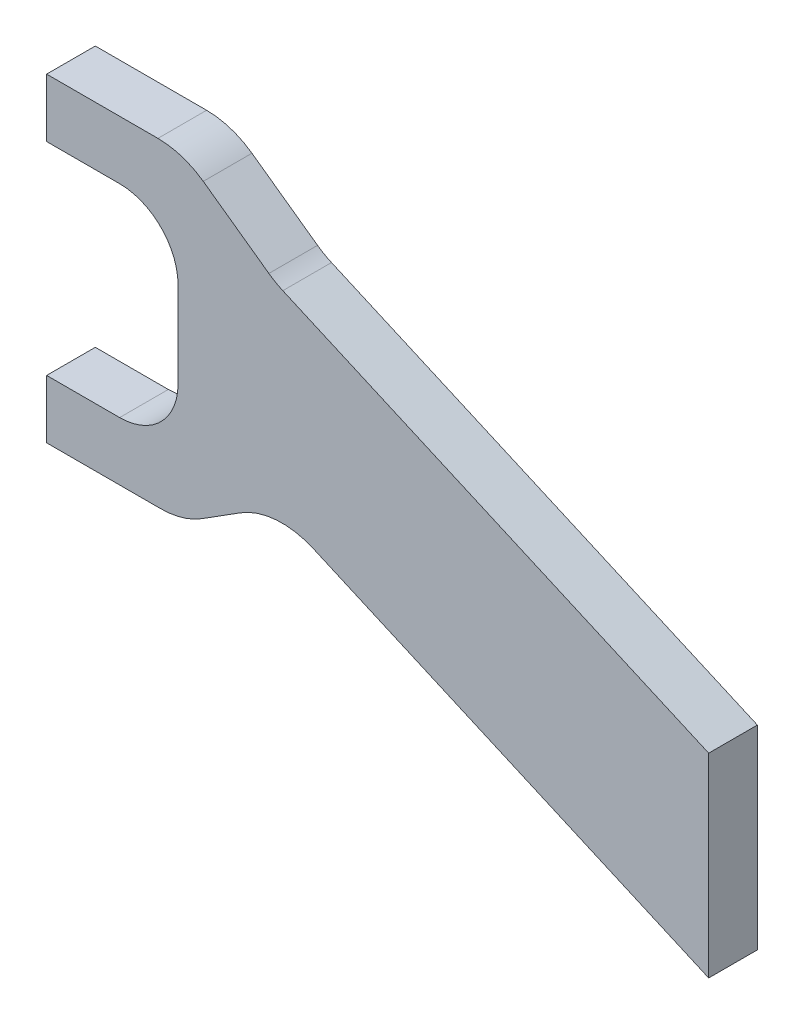
SolidWorks part; units mm, degrees
material "PBT General Purpose"
ref_plane "Front Plane" through (0, 0, 0) normal (0, 0, 1) x (1, 0, 0)
ref_plane "Top Plane" through (0, 0, 0) normal (0, 1, 0) x (1, 0, 0)
ref_plane "Right Plane" through (0, 0, 0) normal (1, 0, 0) x (0, 0, -1)
sketch "frame_outline" plane through (0, 0, 0) normal (0, 0, 1) x (1, 0, 0)
  line L89 (0, 1.64) -> (0, 1.34)
  line L99 (0, 1.34) -> (0.675, 1.34)
  line L100 (0.675, 1.34) -> (0.675, 0.3)
  line L101 (0.675, 0.3) -> (0, 0.3)
  line L102 (0, 0.3) -> (0, 0)
  line L103 (0, 0) -> (0.7, 0)
  line L104 (0.7, 0) -> (1.175, 0.3)
  line L105 (1.175, 0.3) -> (3.4, -0.68)
  line L106 (3.4, -0.68) -> (3.4, 0.32)
  line L107 (3.4, 0.32) -> (1.175, 1.3)
  line L108 (1.175, 1.3) -> (0.7, 1.64)
  line L109 (0.7, 1.64) -> (0, 1.64)
  line L110 (0.675, 0.82) -> (3.9765, 0.82) construction
  point P24 (3.4, -0.18)
  dimension "D1" = 0.3
  dimension "D2" = 0.3
  dimension "D9" = 1.64
  dimension "D10" = 0.675
  dimension "D11" = 1
  dimension "D12" = 1
  dimension "D14" = 0.7
  dimension "D15" = 0.7
  dimension "D16" = 0.5
  dimension "D3" = 3.4
extrude "Boss-Extrude1" add sketch "frame_outline" along normal mid plane 0.25
fillet "Fillet1" radius 0.3 2 edges at (0.675, 0.3, 0) (0.675, 1.34, 0)
fillet "Fillet2" radius 0.4 4 edges at (0.7, 0, 0) (1.175, 0.3, 0) (1.175, 1.3, 0) (0.7, 1.64, 0)
equation "\"t\"= 0.25'thickness of the sheets"
equation "\"t_cf\"= 0.115'thickness of single carbon fiber layer"
equation "\"t_kapton\"= 0.025'thickness of single Kapton flex layer"
equation "\"t_fr4\"= 0.1'thickness of FR4 with copper layer"
equation "\"joint_flex\"= 0.1'Width of flextures gap"
equation "\"joint_flex_eff\"= 0.02'Width of flecture after castelation"
equation "\"joint_fold\"= 0.2'Width of folding joints for 90deg fold"
equation "\"gap_tolerance\"= 0.002'Width to have interfecence fit between carbon fiber inserts"
equation "\"assemble_angle\"= 90'Angle of assembly parts"
equation "\"D1@Boss-Extrude1\"=\"t\""
equation "\"D10@frame_outline\"=\"t\"*1.5+0.3+0.1-\"joint_flex\""
equation "\"link_lift\"= 0.5'Actuation linkage amplification for the lift motion"
equation "\"link_swing\"= 0.45'Actuation linkage amplification for the swing motion"
